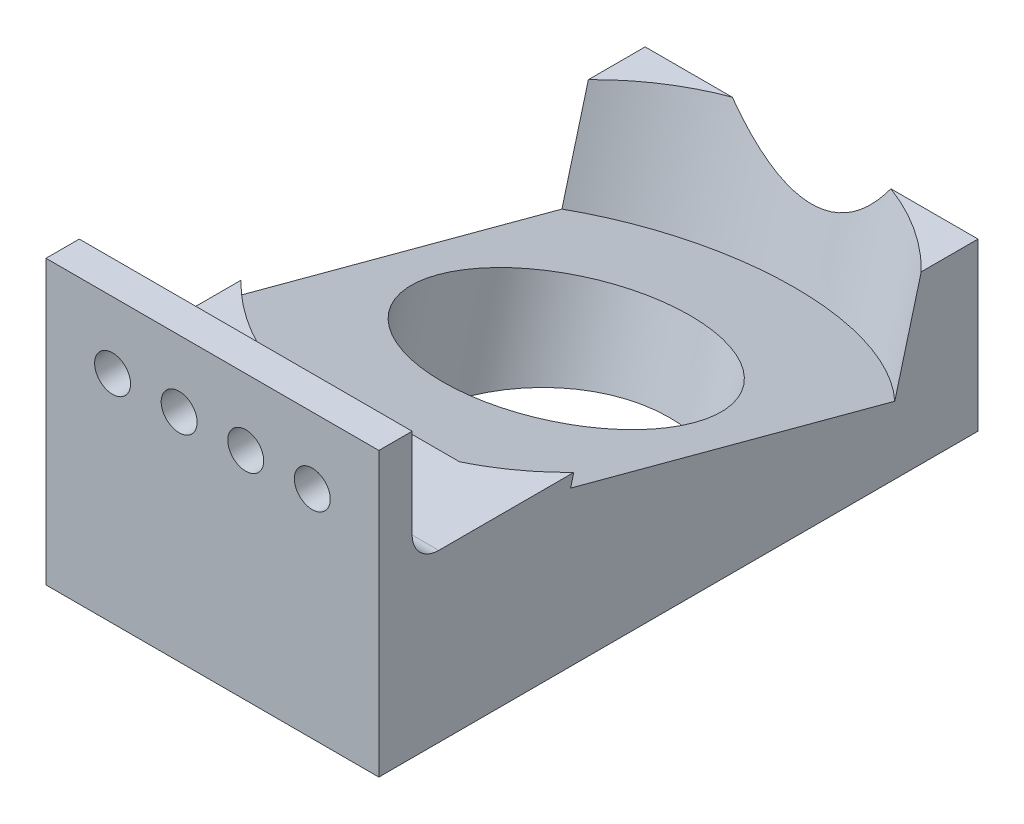
SolidWorks part; units mm, degrees
ref_plane "Front Plane" through (0, 0, 0) normal (0, 0, 1) x (1, 0, 0)
ref_plane "Top Plane" through (0, 0, 0) normal (0, 1, 0) x (1, 0, 0)
ref_plane "Right Plane" through (0, 0, 0) normal (1, 0, 0) x (0, 0, -1)
sketch "Sketch1" plane through (0, 0, 0) normal (1, 0, 0) x (0, 0, -1)
  line L1 (53.975, 15.875) -> (-53.975, 15.875)
  line L2 (53.975, 15.875) -> (53.975, -15.875)
  line L3 (53.975, -15.875) -> (-53.975, -15.875)
  line L4 (-53.975, 15.875) -> (-53.975, -15.875)
  line L5 (53.975, 15.875) -> (-53.975, -15.875) construction
  line L6 (53.975, -15.875) -> (-53.975, 15.875) construction
  point P0 (0, 0)
  dimension "D1" = 31.75
  dimension "D2" = 107.95
extrude "Boss-Extrude1" add sketch "Sketch1" along normal mid plane 63.5
sketch "Sketch2" plane through (0, 0, 0) normal (1, 0, 0) x (0, 0, -1)
  line L0 (0, -21.4654) -> (17.3249, 43.1921) construction
  line L1 (0, 0) -> (0, -41.4309) construction
  line L3 (30.7871, -1.0243) -> (21.7095, -34.9025)
  line L4 (21.7095, -34.9025) -> (-1.905, -28.575)
  line L5 (-1.905, -28.575) -> (15.9342, 38.0017)
  line L8 (53.975, -15.875) -> (53.975, 15.875) construction
  line L9 (-53.975, -15.875) -> (53.975, -15.875) construction
  line L10 (30.7871, -1.0243) -> (50.7214, -6.3656)
  line L11 (50.7214, -6.3656) -> (59.4829, 26.3328)
  line L12 (59.4829, 26.3328) -> (15.9342, 38.0017)
  dimension "D1" = 15
  dimension "D2" = 48.895
  dimension "D3" = 55.88
  dimension "D4" = 12.7
  dimension "D5" = 90.17
revolve "Cut-Revolve1" cut sketch "Sketch2" angle 360 about L0
sketch "Sketch3" plane through (0, 0, 53.975) normal (0, 0, 1) x (1, 0, 0)
  line L0 (31.75, 15.875) -> (31.75, -15.875) construction
  line L1 (-31.75, -38.1) -> (31.75, -38.1)
  line L2 (-31.75, -38.1) -> (-31.75, 38.1)
  line L3 (-31.75, 38.1) -> (31.75, 38.1)
  line L4 (31.75, -38.1) -> (31.75, 38.1)
  line L5 (-31.75, -38.1) -> (31.75, 38.1) construction
  line L6 (-31.75, 38.1) -> (31.75, -38.1) construction
  circle A0 centre (-19.05, 25.4) radius 3.429
  circle A1 centre (-6.35, 25.4) radius 3.429
  circle A2 centre (6.35, 25.4) radius 3.429
  circle A3 centre (19.05, 25.4) radius 3.429
  circle A4 centre (-6.35, -25.4) radius 3.429
  circle A5 centre (6.35, -25.4) radius 3.429
  circle A6 centre (19.05, -25.4) radius 3.429
  circle A7 centre (-19.05, -25.4) radius 3.429
  point P0 (0, 0)
  dimension "D2" = 6.858
  dimension "D1" = 76.2
  dimension "D3" = 12.7
  dimension "D4" = 12.7
  dimension "D5" = 4
  dimension "D6" = 2
extrude "Boss-Extrude2" add sketch "Sketch3" along normal blind 6.35
fillet "Fillet1" radius 5.08 2 edges at (0, 15.875, 53.975) (0, -15.875, 53.975)
sketch "Sketch4" plane through (0, 0, 53.975) normal (0, 0, -1) x (-1, 0, 0)
  line L0 (-31.75, -15.875) -> (31.75, -15.875) construction
  line L1 (-39.59, -15.875) -> (38.5215, -15.875)
  line L2 (-39.59, -15.875) -> (-39.59, -42.4751)
  line L3 (-39.59, -42.4751) -> (38.5215, -42.4751)
  line L4 (38.5215, -15.875) -> (38.5215, -42.4751)
extrude "Cut-Extrude1" cut sketch "Sketch4" against normal through all both and the other way through all
